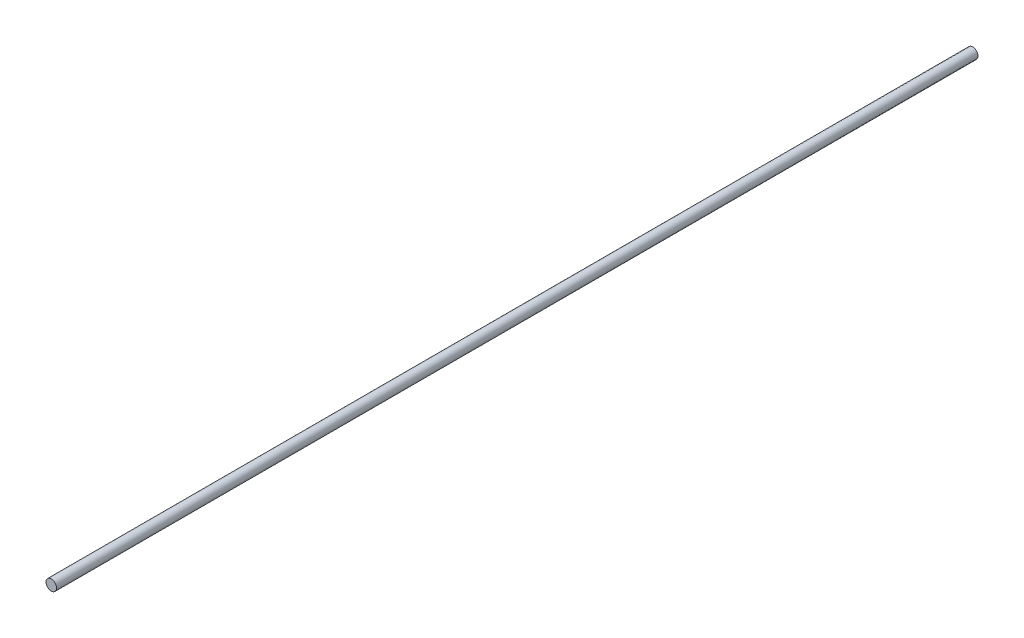
SolidWorks part; units mm, degrees
ref_plane "Спереди" through (0, 0, 0) normal (0, 0, 1) x (1, 0, 0)
ref_plane "Сверху" through (0, 0, 0) normal (0, 1, 0) x (1, 0, 0)
ref_plane "Справа" through (0, 0, 0) normal (1, 0, 0) x (0, 0, -1)
sketch "Эскиз1" plane through (0, 0, 0) normal (0, 0, 1) x (1, 0, 0)
  circle A0 centre (0, 0) radius 4
  dimension "D1" = 8
extrude "Бобышка-Вытянуть1" add sketch "Эскиз1" along normal blind 700
